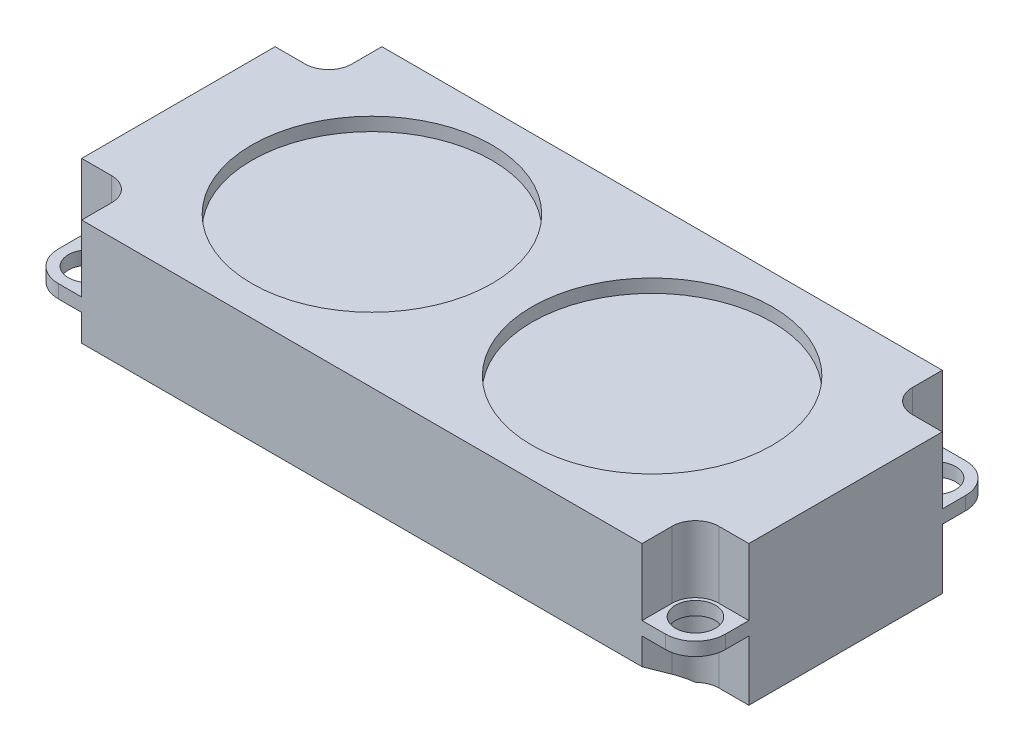
SolidWorks part; units mm, degrees
ref_plane "Ebene vorne" through (0, 0, 0) normal (0, 0, 1) x (1, 0, 0)
ref_plane "Ebene oben" through (0, 0, 0) normal (0, 1, 0) x (1, 0, 0)
ref_plane "Ebene rechts" through (0, 0, 0) normal (1, 0, 0) x (0, 0, -1)
sketch "Sketch1" plane through (0, 0, 0) normal (0, 1, 0) x (1, 0, 0)
  line L1 (-50, -22.5) -> (50, -22.5)
  line L2 (-50, -22.5) -> (-50, 22.5)
  line L3 (-50, 22.5) -> (50, 22.5)
  line L4 (50, -22.5) -> (50, 22.5)
  line L5 (-50, -22.5) -> (50, 22.5) construction
  line L6 (-50, 22.5) -> (50, -22.5) construction
  point P0 (0, 0)
  dimension "D1" = 100
  dimension "D2" = 45
extrude "Boss-Extrude1" add sketch "Sketch1" along normal blind 21
sketch "Sketch2" plane through (50, 0, 0) normal (1, 0, 0) x (0, 0, -1)
  line L0 (-22.5, 0) -> (-22.5, 5)
  line L1 (-22.5, 21) -> (-22.5, 0) construction
  line L2 (-22.5, 5) -> (-15.5, 0)
  line L3 (-22.5, 0) -> (-15.5, 0)
  line L4 (-22.5, 0) -> (22.5, 0) construction
  line L5 (-22.5, 21) -> (22.5, 21) construction
  line L6 (0, 0) -> (0, 21) construction
  line L7 (22.5, 0) -> (15.5, 0)
  line L8 (22.5, 5) -> (15.5, 0)
  line L9 (22.5, 0) -> (22.5, 5)
  dimension "D1" = 16
  dimension "D2" = 31
extrude "Cut-Extrude1" cut sketch "Sketch2" against normal through all
sketch "Sketch3" plane through (0, 21, 0) normal (0, 1, 0) x (1, 0, 0)
  line L0 (-42, 22.5) -> (-42, 18)
  line L1 (50, 22.5) -> (-50, 22.5) construction
  line L2 (-45.5, 14.5) -> (-50, 14.5)
  line L3 (-50, 22.5) -> (-50, -22.5) construction
  line L4 (-50, 14.5) -> (-50, 22.5)
  line L5 (-50, 22.5) -> (-42, 22.5)
  line L6 (0, 0) -> (0, 22.5) construction
  line L7 (0, 0) -> (-50, 0) construction
  line L8 (-50, -22.5) -> (-42, -22.5)
  line L9 (-50, -14.5) -> (-50, -22.5)
  line L10 (-45.5, -14.5) -> (-50, -14.5)
  line L11 (-42, -22.5) -> (-42, -18)
  line L12 (42, -22.5) -> (42, -18)
  line L13 (45.5, -14.5) -> (50, -14.5)
  line L14 (50, -14.5) -> (50, -22.5)
  line L15 (50, -22.5) -> (42, -22.5)
  line L16 (50, 22.5) -> (42, 22.5)
  line L17 (50, 14.5) -> (50, 22.5)
  line L18 (45.5, 14.5) -> (50, 14.5)
  line L19 (42, 22.5) -> (42, 18)
  arc A0 (-42, 18) -> (-45.5, 14.5) centre (-45.5, 18) cw
  arc A1 (-42, -18) -> (-45.5, -14.5) centre (-45.5, -18) ccw
  arc A2 (42, -18) -> (45.5, -14.5) centre (45.5, -18) cw
  arc A3 (42, 18) -> (45.5, 14.5) centre (45.5, 18) ccw
  dimension "D3" = 3.5
  dimension "D1" = 8
  dimension "D2" = 8
extrude "Cut-Extrude2" cut sketch "Sketch3" against normal blind 10
ref_plane "Plane1" through (0, 9, 0) normal (0, 1, 0) x (1, 0, 0)
sketch "Sketch5" plane through (0, 9, 0) normal (0, 1, 0) x (1, 0, 0)
  line L0 (-45.5, -14.5) -> (-50, -14.5) construction
  line L1 (-50, -14.5) -> (-50, -22.5) construction
  line L2 (-50, -22.5) -> (-42, -22.5) construction
  line L3 (-42, -22.5) -> (-42, -18) construction
  line L4 (42, -18) -> (42, -22.5) construction
  line L5 (42, -22.5) -> (50, -22.5) construction
  line L6 (50, -22.5) -> (50, -14.5) construction
  line L7 (50, -14.5) -> (45.5, -14.5) construction
  line L8 (45.5, 14.5) -> (50, 14.5) construction
  line L9 (50, 14.5) -> (50, 22.5) construction
  line L10 (50, 22.5) -> (42, 22.5) construction
  line L11 (42, 22.5) -> (42, 18) construction
  line L12 (-42, 22.5) -> (-50, 22.5) construction
  line L13 (-50, 22.5) -> (-50, 14.5) construction
  line L14 (-50, 14.5) -> (-45.5, 14.5) construction
  line L15 (-42, 18) -> (-42, 22.5) construction
  line L16 (-45.5, -14.5) -> (-50, -14.5)
  line L17 (-50, -14.5) -> (-50, -22.5)
  line L18 (-50, -22.5) -> (-42, -22.5)
  line L19 (-42, -22.5) -> (-42, -18)
  line L20 (42, -18) -> (42, -22.5)
  line L21 (42, -22.5) -> (50, -22.5)
  line L22 (50, -22.5) -> (50, -14.5)
  line L23 (50, -14.5) -> (45.5, -14.5)
  line L24 (45.5, 14.5) -> (50, 14.5)
  line L25 (50, 14.5) -> (50, 22.5)
  line L26 (50, 22.5) -> (42, 22.5)
  line L27 (42, 22.5) -> (42, 18)
  line L28 (-42, 22.5) -> (-50, 22.5)
  line L29 (-50, 22.5) -> (-50, 14.5)
  line L30 (-50, 14.5) -> (-45.5, 14.5)
  line L31 (-42, 18) -> (-42, 22.5)
  arc A0 (-42, -18) -> (-45.5, -14.5) centre (-45.5, -18) ccw construction
  arc A1 (45.5, -14.5) -> (42, -18) centre (45.5, -18) ccw construction
  arc A2 (42, 18) -> (45.5, 14.5) centre (45.5, 18) ccw construction
  arc A3 (-45.5, 14.5) -> (-42, 18) centre (-45.5, 18) ccw construction
  arc A4 (-42, -18) -> (-45.5, -14.5) centre (-45.5, -18) ccw
  arc A5 (45.5, -14.5) -> (42, -18) centre (45.5, -18) ccw
  arc A6 (42, 18) -> (45.5, 14.5) centre (45.5, 18) ccw
  arc A7 (-45.5, 14.5) -> (-42, 18) centre (-45.5, 18) ccw
extrude "Cut-Extrude3" cut sketch "Sketch5" against normal through all
sketch "Sketch6" plane through (0, 11, 0) normal (0, 1, 0) x (1, 0, 0)
  line L0 (-45.5, 18) -> (-48.5, 18) construction
  line L1 (-45.5, 18) -> (-45.5, 21) construction
  line L2 (-50, 22.5) -> (-50, 14.5) construction
  line L4 (-11.55, 0) -> (11.55, 0) construction
  line L5 (0, -11.55) -> (0, 11.55) construction
  line L6 (45.5, 18) -> (45.5, 21) construction
  line L7 (45.5, 18) -> (48.5, 18) construction
  circle A0 centre (-45.5, 18) radius 3
  arc A3 (-45.5, 14.5) -> (-42, 18) centre (-45.5, 18) ccw construction
  circle A4 centre (-45.5, -18) radius 3
  circle A5 centre (45.5, -18) radius 3
  circle A6 centre (45.5, 18) radius 3
  point P11 (-45.6244, 18.0444)
  dimension "D1" = 1.5
extrude "Cut-Extrude4" cut sketch "Sketch6" against normal through all
fillet "Fillet1" radius 4.5 4 edges at (50, 10, -22.5) (50, 10, 22.5) (-50, 10, 22.5) (-50, 10, -22.5)
sketch "Sketch7" plane through (0, 21, 0) normal (0, 1, 0) x (1, 0, 0)
  line L0 (-3, 0) -> (3, 0) construction
  circle A0 centre (-21, 0) radius 18
  circle A1 centre (21, 0) radius 18
  dimension "D1" = 36
  dimension "D2" = 36
  dimension "D3" = 6
extrude "Cut-Extrude5" cut sketch "Sketch7" against normal blind 2
